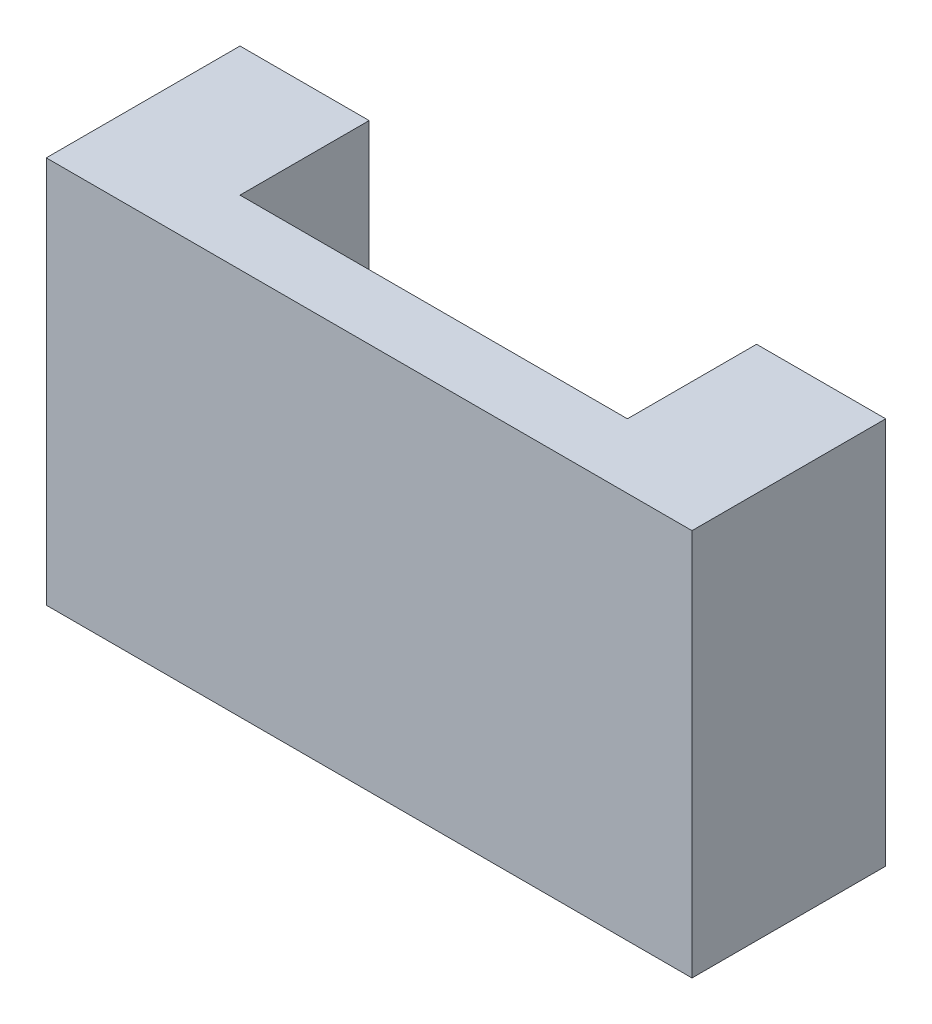
SolidWorks part; units mm, degrees
ref_plane "Přední rovina" through (0, 0, 0) normal (0, 0, 1) x (1, 0, 0)
ref_plane "Horní rovina" through (0, 0, 0) normal (0, 1, 0) x (1, 0, 0)
ref_plane "Pravá rovina" through (0, 0, 0) normal (1, 0, 0) x (0, 0, -1)
sketch "Sketch1" plane through (0, 0, 0) normal (0, 1, 0) x (1, 0, 0)
  line L1 (-25, 0) -> (-15, 0)
  line L2 (-25, 0) -> (-25, -15)
  line L3 (-25, -15) -> (25, -15)
  line L6 (-15, 0) -> (-15, -10)
  line L7 (-15, -10) -> (15, -10)
  line L9 (0, 0) -> (0, -15) construction
  line L10 (15, 0) -> (15, -10)
  line L11 (25, 0) -> (25, -15)
  line L12 (25, 0) -> (15, 0)
  point P3 (0, -10)
  dimension "D1" = 25
  dimension "D2" = 10
  dimension "D3" = 10
  dimension "D4" = 5
extrude "Boss-Extrude1" add sketch "Sketch1" along normal blind 30
